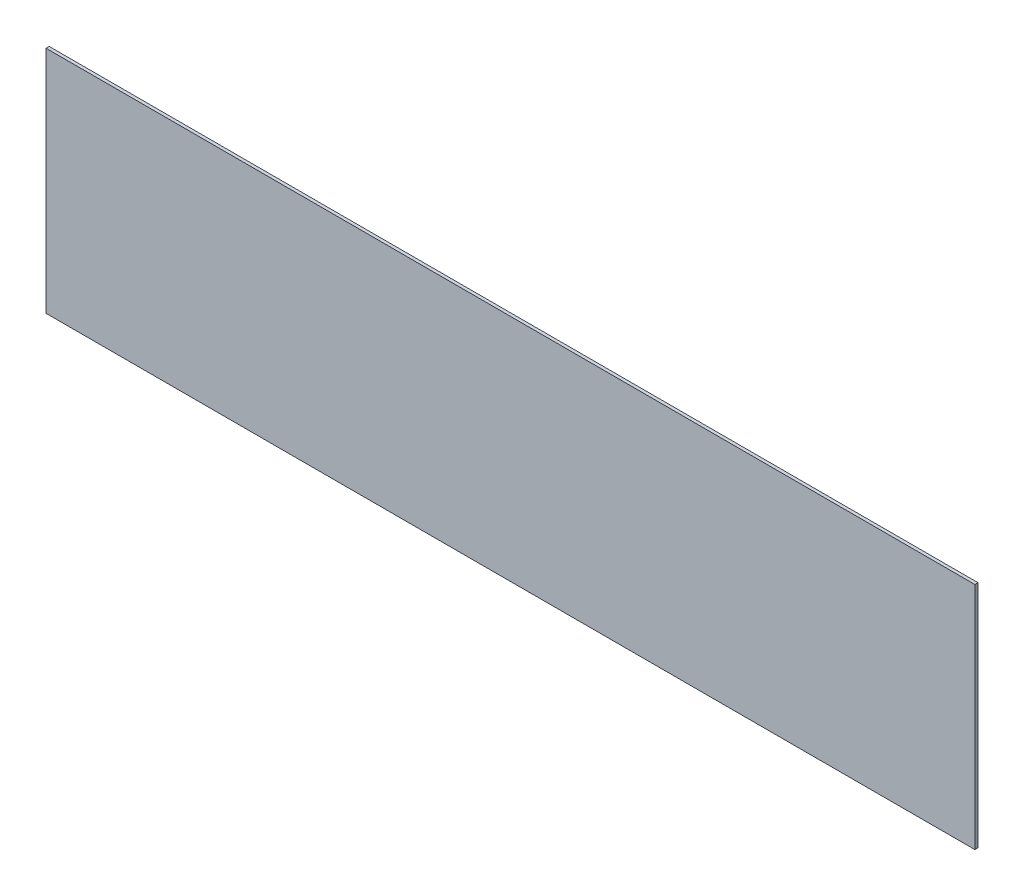
SolidWorks part; units mm, degrees
ref_plane "Front Plane" through (0, 0, 0) normal (0, 0, 1) x (1, 0, 0)
ref_plane "Top Plane" through (0, 0, 0) normal (0, 1, 0) x (1, 0, 0)
ref_plane "Right Plane" through (0, 0, 0) normal (1, 0, 0) x (0, 0, -1)
sketch "Sketch2" plane through (0, 0, 0) normal (0, 0, 1) x (1, 0, 0)
  line L5 (-445, 110) -> (445, 110)
  line L6 (-445, 110) -> (-445, -110)
  line L7 (-445, -110) -> (445, -110)
  line L8 (445, 110) -> (445, -110)
  dimension "D1" = 220
  dimension "D2" = 890
  dimension "D3" = 445
  dimension "D4" = 110
extrude "Boss-Extrude1" add sketch "Sketch2" along normal blind 3
